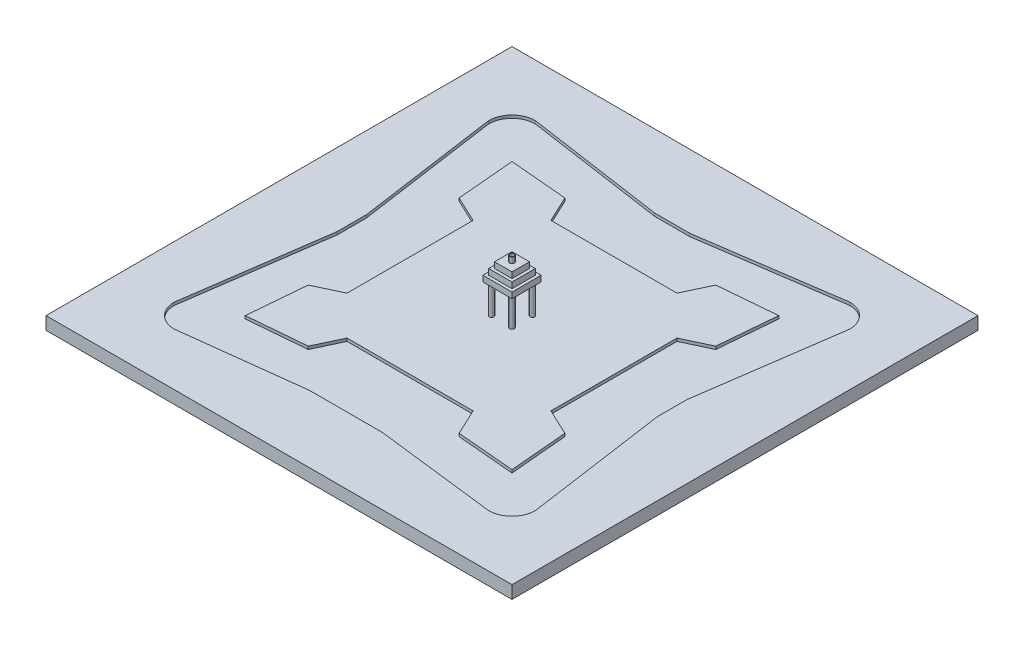
SolidWorks part; units mm, degrees
ref_plane "Front Plane" through (0, 0, 0) normal (0, 0, 1) x (1, 0, 0)
ref_plane "Top Plane" through (0, 0, 0) normal (0, 1, 0) x (1, 0, 0)
ref_plane "Right Plane" through (0, 0, 0) normal (1, 0, 0) x (0, 0, -1)
sketch "Sketch1" plane through (0, 0, 0) normal (0, 1, 0) x (1, 0, 0)
  line L1 (-4000, -4000) -> (4000, -4000)
  line L2 (-4000, -4000) -> (-4000, 4000)
  line L3 (-4000, 4000) -> (4000, 4000)
  line L4 (4000, -4000) -> (4000, 4000)
  line L5 (-4000, -4000) -> (4000, 4000) construction
  line L6 (-4000, 4000) -> (4000, -4000) construction
  point P0 (0, 0)
  dimension "D1" = 8000
extrude "Ground Floor" add sketch "Sketch1" along normal blind 220
sketch "Sketch2" plane through (0, 220, 0) normal (0, 1, 0) x (1, 0, 0)
  line L0 (0, -4000) -> (0, 4000) construction
  line L1 (-4000, -4000) -> (4000, -4000) construction
  line L2 (4000, 4000) -> (-4000, 4000) construction
  line L3 (-4000, 0) -> (4000, 0) construction
  line L4 (-4000, 4000) -> (-4000, -4000) construction
  line L5 (4000, -4000) -> (4000, 4000) construction
  line L6 (-2700, -2700) -> (2700, -2700) construction
  line L7 (-625, -2850) -> (625, -2850)
  line L8 (-2700, -3100) -> (-625, -2850)
  line L9 (625, -2850) -> (2700, -3100)
  line L10 (-2750, -250) -> (-2750, 250)
  line L11 (-3100, -2700) -> (-2750, -250)
  line L12 (-3100, 2700) -> (-2750, 250)
  line L13 (2750, -250) -> (2750, 250)
  line L14 (3100, -2700) -> (2750, -250)
  line L15 (3100, 2700) -> (2750, 250)
  line L16 (-300, 2750) -> (300, 2750)
  line L17 (-2700, 3100) -> (-300, 2750)
  line L18 (300, 2750) -> (2700, 3100)
  arc A0 (-3100, -2700) -> (-2700, -3100) centre (-2700, -2700) ccw
  arc A1 (-2700, 3100) -> (-3100, 2700) centre (-2700, 2700) ccw
  arc A2 (3100, 2700) -> (2700, 3100) centre (2700, 2700) ccw
  arc A3 (2700, -3100) -> (3100, -2700) centre (2700, -2700) ccw
  point P23 (0, 0)
  point P28 (0, -2850)
  point P30 (-2750, 0)
  point P39 (0, 2750)
  dimension "D1" = 800
  dimension "D3" = 5400
  dimension "D4" = 1250
  dimension "D5" = 1150
  dimension "D6" = 500
  dimension "D7" = 1250
  dimension "D8" = 600
  dimension "D9" = 1250
  dimension "D2" = 4
extrude "Moat" cut sketch "Sketch2" against normal blind 50
sketch "Sketch3" plane through (0, 170, 0) normal (0, 1, 0) x (1, 0, 0)
  line L0 (0, -4000) -> (0, 4000) construction
  line L1 (-4000, -4000) -> (4000, -4000) construction
  line L2 (4000, 4000) -> (-4000, 4000) construction
  line L3 (-4000, 0) -> (4000, 0) construction
  line L4 (-4000, 4000) -> (-4000, -4000) construction
  line L5 (4000, -4000) -> (4000, 4000) construction
  line L6 (-4000, -4000) -> (4000, 4000) construction
  line L7 (-4000, 4000) -> (4000, -4000) construction
  line L8 (-2290, -2290) -> (-1295, -2203)
  line L9 (-1295, -2203) -> (-1082.5, -1750)
  line L10 (-1082.5, -1750) -> (0, -1750)
  line L11 (-1750, -1082.5) -> (-1750, 0)
  line L12 (-2203, -1295) -> (-1750, -1082.5)
  line L13 (-2290, -2290) -> (-2203, -1295)
  line L14 (-1082.5, 1750) -> (0, 1750)
  line L15 (-1295, 2203) -> (-1082.5, 1750)
  line L16 (-2290, 2290) -> (-1295, 2203)
  line L17 (-2290, 2290) -> (-2203, 1295)
  line L18 (-2203, 1295) -> (-1750, 1082.5)
  line L19 (-1750, 1082.5) -> (-1750, 0)
  line L20 (1750, 1082.5) -> (1750, 0)
  line L21 (2203, 1295) -> (1750, 1082.5)
  line L22 (2290, 2290) -> (2203, 1295)
  line L23 (2290, 2290) -> (1295, 2203)
  line L24 (1295, 2203) -> (1082.5, 1750)
  line L25 (1082.5, 1750) -> (0, 1750)
  line L26 (1082.5, -1750) -> (0, -1750)
  line L27 (1295, -2203) -> (1082.5, -1750)
  line L28 (2290, -2290) -> (1295, -2203)
  line L29 (2290, -2290) -> (2203, -1295)
  line L30 (2203, -1295) -> (1750, -1082.5)
  line L31 (1750, -1082.5) -> (1750, 0)
  line L32 (-2290, -2290) -> (2290, -2290) construction
  point P51 (0, 0)
  dimension "D1" = 4
  dimension "D2" = 4580
  dimension "D3" = 87
  dimension "D4" = 2590
  dimension "D5" = 2165
  dimension "D6" = 2250
extrude "Citadel" add sketch "Sketch3" along normal blind 50
sketch "Sketch6" plane through (0, 220, 0) normal (0, 1, 0) x (1, 0, 0)
  line L0 (-4000, -4000) -> (4000, 4000) construction
  line L1 (-4000, 4000) -> (4000, -4000) construction
  circle A0 centre (-175, -175) radius 40
  circle A1 centre (-175, 175) radius 40
  circle A2 centre (175, 175) radius 40
  circle A3 centre (175, -175) radius 40
  point P10 (0, 0)
  point P19 (0, 0)
  dimension "D2" = 80
  dimension "D3" = 350
  dimension "D1" = 4
extrude "Boss-Extrude1" add sketch "Sketch6" along normal blind 500
sketch "Sketch7" plane through (0, 720, 0) normal (0, 1, 0) x (1, 0, 0)
  line L1 (-250, -250) -> (250, -250)
  line L2 (-250, -250) -> (-250, 250)
  line L3 (-250, 250) -> (250, 250)
  line L4 (250, -250) -> (250, 250)
  line L5 (-250, -250) -> (250, 250) construction
  line L6 (-250, 250) -> (250, -250) construction
  point P0 (0, 0)
  dimension "D1" = 500
extrude "Boss-Extrude2" add sketch "Sketch7" along normal blind 100 separate body
sketch "Sketch8" plane through (0, 820, 0) normal (0, 1, 0) x (1, 0, 0)
  line L1 (-200, -200) -> (200, -200)
  line L2 (-200, -200) -> (-200, 200)
  line L3 (-200, 200) -> (200, 200)
  line L4 (200, -200) -> (200, 200)
  line L5 (-200, -200) -> (200, 200) construction
  line L6 (-200, 200) -> (200, -200) construction
  point P0 (0, 0)
  dimension "D1" = 400
extrude "Boss-Extrude3" add sketch "Sketch8" along normal blind 100
sketch "Sketch9" plane through (0, 920, 0) normal (0, 1, 0) x (1, 0, 0)
  line L1 (-150, -150) -> (150, -150)
  line L2 (-150, -150) -> (-150, 150)
  line L3 (-150, 150) -> (150, 150)
  line L4 (150, -150) -> (150, 150)
  line L5 (-150, -150) -> (150, 150) construction
  line L6 (-150, 150) -> (150, -150) construction
  point P0 (0, 0)
  dimension "D1" = 300
extrude "Boss-Extrude4" add sketch "Sketch9" along normal blind 100
sketch "Sketch10" plane through (0, 1020, 0) normal (0, 1, 0) x (1, 0, 0)
  circle A0 centre (0, 0) radius 40
  circle A1 centre (0, 0) radius 35
  dimension "D1" = 80
  dimension "D2" = 5
extrude "Boss-Extrude5" add sketch "Sketch10" along normal blind 100
